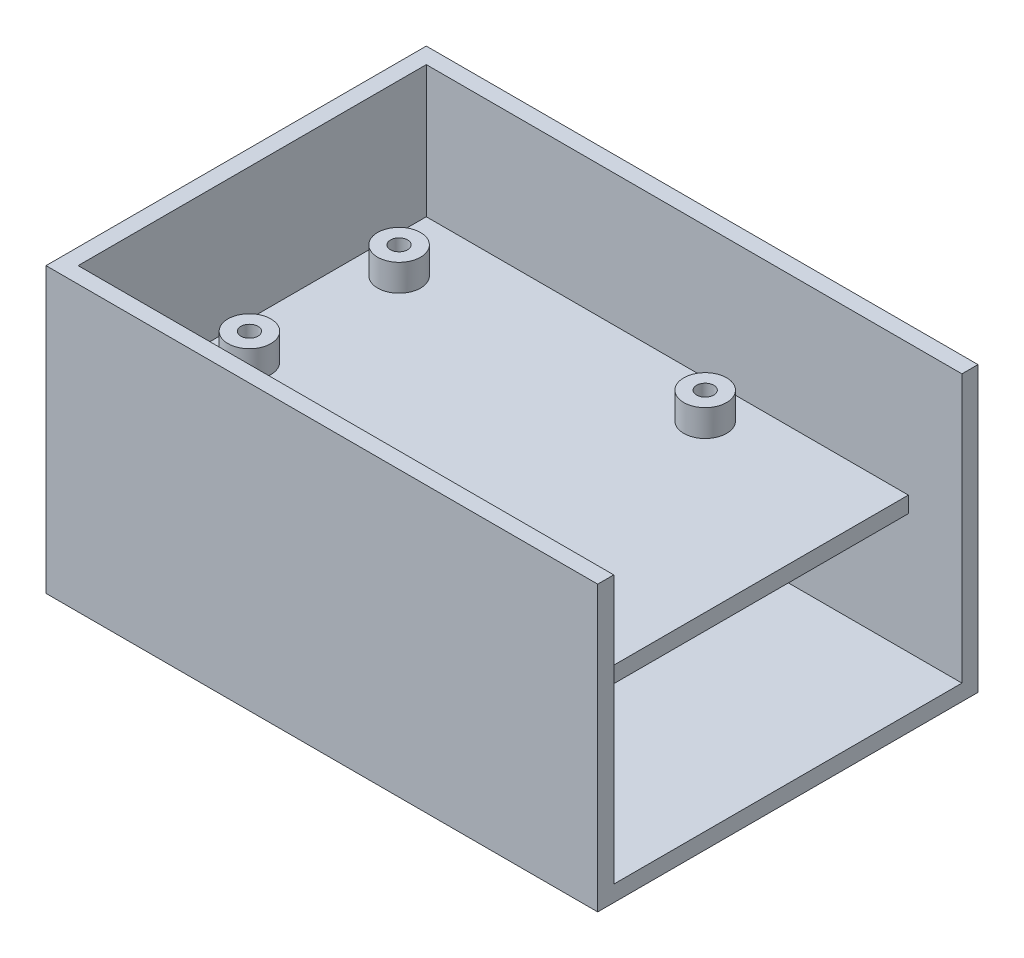
SolidWorks part; units mm, degrees
ref_plane "Front Plane" through (0, 0, 0) normal (0, 0, 1) x (1, 0, 0)
ref_plane "Top Plane" through (0, 0, 0) normal (0, 1, 0) x (1, 0, 0)
ref_plane "Right Plane" through (0, 0, 0) normal (1, 0, 0) x (0, 0, -1)
sketch "Sketch2" plane through (0, 0, 0) normal (0, 1, 0) x (1, 0, 0)
  line L1 (-50, 32.5) -> (50, 32.5)
  line L2 (-50, 32.5) -> (-50, -32.5)
  line L3 (-50, -32.5) -> (50, -32.5)
  line L4 (50, 32.5) -> (50, -32.5)
  line L5 (-50, 32.5) -> (50, -32.5) construction
  line L6 (-50, -32.5) -> (50, 32.5) construction
  point P0 (0, 0)
  dimension "D1" = 100
  dimension "D2" = 65
extrude "Boss-Extrude1" add sketch "Sketch2" along normal blind 50
shell "Shell1" thickness 3
sketch "Sketch7" plane through (-50, 0, 0) normal (1, 0, 0) x (0, 0, -1)
  line L0 (32.5, 50) -> (32.5, 0) construction
  line L1 (-32.5, 25.4) -> (32.5, 25.4)
  line L2 (-32.5, 25.4) -> (-32.5, 22.4)
  line L3 (-32.5, 22.4) -> (32.5, 22.4)
  line L4 (32.5, 25.4) -> (32.5, 22.4)
  line L5 (-32.5, 25.4) -> (32.5, 22.4) construction
  line L6 (-32.5, 22.4) -> (32.5, 25.4) construction
  line L8 (-32.5, 50) -> (-32.5, 0) construction
  line L9 (32.5, 0) -> (-32.5, 0) construction
  point P0 (0, 23.9)
  point P7 (0, 0)
  dimension "D1" = 3
  dimension "D2" = 22.4
extrude "Boss-Extrude3" add sketch "Sketch7" along normal up to surface (100 mm away) up to face at (50, 24.25, 0)
sketch "Sketch3" plane through (0, 25.4, 0) normal (0, 1, 0) x (1, 0, 0)
  line L0 (50, 32.5) -> (-50, 32.5) construction
  line L1 (50, -32.5) -> (40, -32.5)
  line L2 (50, -32.5) -> (50, 32.5)
  line L3 (50, 32.5) -> (40, 32.5)
  line L4 (40, -32.5) -> (40, 32.5)
  line L5 (50, -32.5) -> (-50, -32.5) construction
  line L6 (50, -32.5) -> (50, 32.5) construction
  dimension "D2" = 10
extrude "Cut-Extrude1" cut sketch "Sketch3" against normal up to next
sketch "Sketch4" plane through (0, 25.4, 0) normal (0, 1, 0) x (1, 0, 0)
  line L2 (40, 32.5) -> (-50, 32.5) construction
  line L3 (-50, 32.5) -> (-50, -32.5) construction
  circle A0 centre (9.07, 25.5) radius 4
  circle A1 centre (9.07, 25.5) radius 1.6
  circle A2 centre (7.8, -22.76) radius 4
  circle A3 centre (7.8, -22.76) radius 1.6
  circle A4 centre (-43, -7.52) radius 4
  circle A5 centre (-43, -7.52) radius 1.6
  circle A6 centre (-43, 20.42) radius 4
  circle A7 centre (-43, 20.42) radius 1.6
  point P12 (0, 0)
  dimension "D1" = 3.2
  dimension "D2" = 8
  dimension "D3" = 27.94
  dimension "D4" = 50.8
  dimension "D5" = 15.24
  dimension "D6" = 48.26
  dimension "D7" = 1.27
  dimension "D8" = 7
  dimension "D9" = 7
extrude "Boss-Extrude4" add sketch "Sketch4" along normal blind 5
